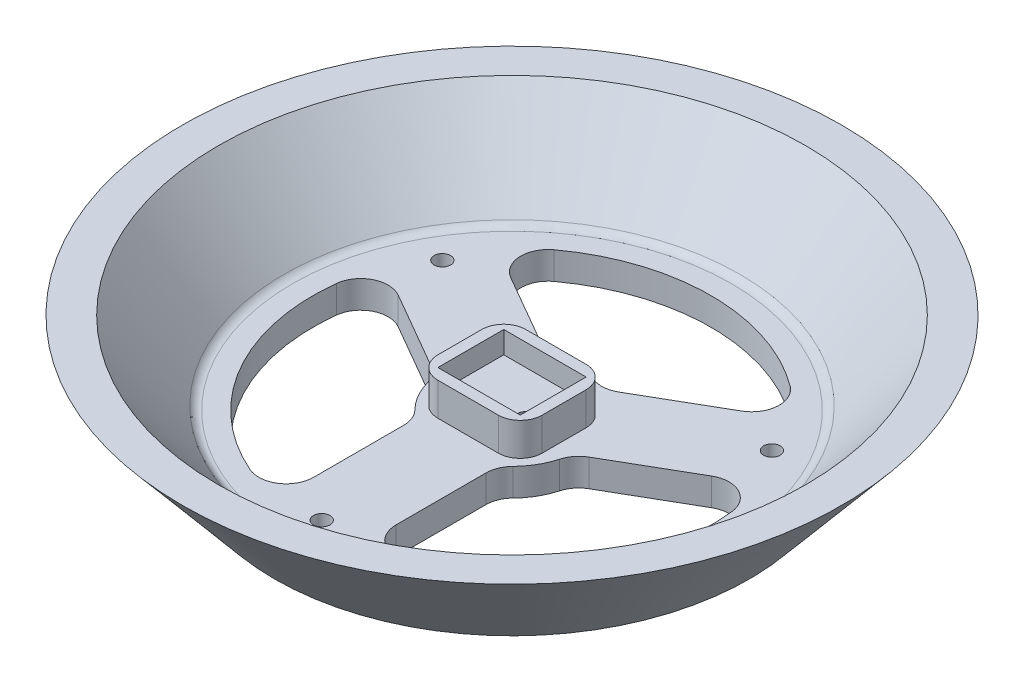
SolidWorks part; units mm, degrees
material "ABS"
ref_plane "Alzado" through (0, 0, 0) normal (0, 0, 1) x (1, 0, 0)
ref_plane "Planta" through (0, 0, 0) normal (0, 1, 0) x (1, 0, 0)
ref_plane "Vista lateral" through (0, 0, 0) normal (1, 0, 0) x (0, 0, -1)
sketch "Sketch1" plane through (0, 0, 0) normal (0, 1, 0) x (1, 0, 0)
  circle A0 centre (0, 0) radius 60
  dimension "D1" = 120
extrude "Boss-Extrude1" add sketch "Sketch1" against normal blind 20 draft 40
shell "Shell1" thickness 5
sketch "Sketch2" plane through (0, -20, 0) normal (0, -1, 0) x (1, 0, 0)
  line L0 (34.4358, -11.2213) -> (12.4103, 1.4952)
  line L2 (-7.5, 35.433) -> (-7.5, 10)
  line L4 (7.5, 35.433) -> (7.5, 10)
  line L6 (26.9358, -24.2117) -> (4.9103, -11.4952)
  line L8 (-26.9358, -24.2117) -> (-4.9103, -11.4952)
  line L10 (-34.4358, -11.2213) -> (-12.4103, 1.4952)
  line L11 (0, 0) -> (0, 36.218) construction
  line L12 (0, 0) -> (31.3657, -18.109) construction
  line L13 (0, 0) -> (-31.3657, -18.109) construction
  arc A0 (12.4103, 1.4952) -> (7.5, 10) centre (0, 0) ccw
  arc A3 (-4.9103, -11.4952) -> (4.9103, -11.4952) centre (0, 0) ccw
  arc A4 (-7.5, 10) -> (-12.4103, 1.4952) centre (0, 0) ccw
  circle A6 centre (0, 0) radius 43.218 construction
  circle A10 centre (0, 0) radius 36.218
  point P18 (0, 0)
  point P21 (0, 0)
  dimension "D1" = 25
  dimension "D5" = 3
  dimension "D8" = 7
  dimension "D2" = 15
  dimension "D4" = 7.5
  dimension "D6" = 7.5
  dimension "D7" = 7.5
  dimension "D3" = 3
extrude "Cut-Extrude2" cut sketch "Sketch2" against normal blind 20 contours L2 A10 L10 A4 | L0 A10 L4 A0 | L8 A10 L6 A3
sketch "Sketch3" plane through (0, -15, 0) normal (0, 1, 0) x (1, 0, 0)
  line L0 (-5.5, -8) -> (5.5, -8)
  line L1 (-7.5, 6) -> (7.5, 6)
  line L2 (-7.5, 6) -> (-7.5, -6)
  line L3 (-7.5, -6) -> (7.5, -6)
  line L4 (7.5, 6) -> (7.5, -6)
  line L5 (-7.5, 6) -> (7.5, -6) construction
  line L6 (-7.5, -6) -> (7.5, 6) construction
  line L7 (9.5, 4) -> (9.5, -4)
  line L8 (-5.5, 8) -> (5.5, 8)
  line L9 (-9.5, 4) -> (-9.5, -4)
  line L10 (-9.5, -8) -> (9.5, -8) construction
  line L11 (9.5, 8) -> (9.5, -8) construction
  line L12 (-9.5, 8) -> (9.5, 8) construction
  line L13 (-9.5, 8) -> (-9.5, -8) construction
  arc A0 (5.5, -8) -> (9.5, -4) centre (5.5, -4) ccw
  arc A1 (-5.5, 8) -> (-9.5, 4) centre (-5.5, 4) ccw
  arc A2 (-5.5, -8) -> (-9.5, -4) centre (-5.5, -4) cw
  arc A3 (9.5, 4) -> (5.5, 8) centre (5.5, 4) ccw
  point P0 (0, 0)
  dimension "D4" = 4
  dimension "D1" = 12
  dimension "D2" = 15
  dimension "D3" = 2
extrude "Boss-Extrude2" add sketch "Sketch3" along normal blind 6
hole_wizard "Ø3.0mm Dowel Hole1" positions "Sketch4" profile "Sketch6" hole size "Ø3.0" standard "ANSI Metric" end condition up to next
sketch "Sketch4" plane through (0, -15, 0) normal (0, 1, 0) x (1, 0, 0)
  line L1 (0, 0) -> (0, -40.8865) construction
  line L3 (0, 0) -> (-35.4087, 20.4432) construction
  line L4 (0, 0) -> (35.4087, 20.4432) construction
  circle A1 centre (0, 0) radius 40.8865 construction
  point P0 (-29.9991, 17.32)
  point P19 (29.9991, 17.32)
  point P20 (0, -34.64)
  dimension "D1" = 34.64
  dimension "D2" = 34.64
  dimension "D5" = 34.64
  dimension "D3" = 3
  dimension "D4" = 3
sketch "Sketch6" plane through (-29.9991, -15, -17.32) normal (1, 0, 0) x (0, 0, 1)
  line L0 (0, 0) -> (0, 5)
  line L1 (0, 5) -> (1.5, 5)
  line L2 (1.5, 5) -> (1.5, 0)
  line L5 (1.5, 0) -> (0, 0)
  line L11 (0, -6.35) -> (0, 107.95) construction
  dimension "Thru Hole Dia." = 3
  dimension "Thru Hole Depth" = 5
sketch "Sketch10" plane through (0, -20, 0) normal (0, -1, 0) x (1, 0, 0)
  line L0 (-6.5, -8) -> (6.5, -8)
  line L1 (-7.5, -6) -> (7.5, -6)
  line L2 (-7.5, -6) -> (-7.5, 6)
  line L3 (-7.5, 6) -> (7.5, 6)
  line L4 (7.5, -6) -> (7.5, 6)
  line L5 (-7.5, -6) -> (7.5, 6) construction
  line L6 (-7.5, 6) -> (7.5, -6) construction
  line L7 (9.5, -5) -> (9.5, 5)
  line L8 (-6.5, 8) -> (6.5, 8)
  line L9 (-9.5, -5) -> (-9.5, 5)
  line L10 (-9.5, -8) -> (9.5, -8) construction
  line L11 (9.5, -8) -> (9.5, 8) construction
  line L12 (-9.5, 8) -> (9.5, 8) construction
  line L13 (-9.5, -8) -> (-9.5, 8) construction
  arc A0 (6.5, -8) -> (9.5, -5) centre (6.5, -5) ccw
  arc A1 (-6.5, 8) -> (-9.5, 5) centre (-6.5, 5) ccw
  arc A2 (-6.5, -8) -> (-9.5, -5) centre (-6.5, -5) cw
  arc A3 (9.5, 5) -> (6.5, 8) centre (6.5, 5) ccw
  point P0 (0, 0)
  dimension "D4" = 3
  dimension "D1" = 15
  dimension "D2" = 12
  dimension "D3" = 2
fillet "Fillet1" radius 5 12 edges at (7.5, -17.5, 10) (12.4103, -17.5, 1.4952) (-7.5, -17.5, 10) (-12.4103, -17.5, 1.4952) (-4.9103, -17.5, -11.4952) (4.9103, -17.5, -11.4952) (-34.4358, -17.5, -11.2213) (-26.9358, -17.5, -24.2117) (34.4358, -17.5, -11.2213) (26.9358, -17.5, -24.2117) (-7.5, -17.5, 35.433) (7.5, -17.5, 35.433)
fillet "Fillet2" radius 2 1 edges at (0, -15, 40.8865)
extrude "Cut-Extrude3" cut sketch "Sketch10" against normal blind 5 contours L2 L1 L4 L3
sketch "Sketch12" plane through (0, 0, 0) normal (1, 0, 0) x (0, 0, -1)
  line L1 (0, -4) -> (0, -16) construction
  line L2 (-6, -16) -> (6, -16)
  line L3 (-6, -16) -> (-6, -13)
  line L4 (-6, -13) -> (6, -13)
  line L5 (6, -16) -> (6, -13)
  line L6 (-6, -9) -> (-6, -20) construction
  line L9 (-3.3583, -15) -> (-8.7482, -15) construction
  line L10 (0, 0) -> (0, -14.2856) construction
  point P10 (0, -10)
  dimension "D1" = 12
  dimension "D2" = 3
  dimension "D3" = 6
  dimension "D4" = 1
extrude "Boss-Extrude5" add sketch "Sketch12" against normal mid plane 15
hole_wizard "Ø3.0mm Dowel Hole2" positions "Sketch8" profile "Sketch9" hole size "Ø3.0" standard "ANSI Metric"
sketch "Sketch8" plane through (0, -15, 0) normal (0, 1, 0) x (1, 0, 0)
  line L0 (-7.5, 6) -> (-7.5, -6) construction
  line L2 (7.5, 6) -> (-7.5, 6) construction
  point P0 (4.5, -2)
  dimension "D1" = 12
  dimension "D2" = 8
sketch "Sketch9" plane through (4.5, -15, 2) normal (1, 0, 0) x (0, 0, -1)
  line L0 (0, 0) -> (0, 15.9013)
  line L1 (0, 15.9013) -> (1.5, 15)
  line L2 (1.5, 15) -> (1.5, 0)
  line L5 (1.5, 0) -> (0, 0)
  line L10 (0, 15.9013) -> (-1.5, 15) construction
  line L11 (0, -6.35) -> (0, 107.95) construction
  dimension "Hole Dia." = 3
  dimension "Hole Depth" = 15
  dimension "Drill Angle" = 118
hole_wizard "Ø3.0mm Dowel Hole3" positions "Sketch13" profile "Sketch14" hole size "Ø3.0" standard "ANSI Metric"
sketch "Sketch13" plane through (0, -15, 0) normal (0, 1, 0) x (1, 0, 0)
  point P0 (4.5, -2)
sketch "Sketch14" plane through (4.5, -15, 2) normal (1, 0, 0) x (0, 0, 1)
  line L0 (0, 0) -> (0, 15.9013)
  line L1 (0, 15.9013) -> (1.5, 15)
  line L2 (1.5, 15) -> (1.5, 0)
  line L5 (1.5, 0) -> (0, 0)
  line L10 (0, 15.9013) -> (-1.5, 15) construction
  line L11 (0, -6.35) -> (0, 107.95) construction
  dimension "Hole Dia." = 3
  dimension "Hole Depth" = 15
  dimension "Drill Angle" = 118
equation "\"Diametro_inferior\"= \"D1@Sketch1\""
